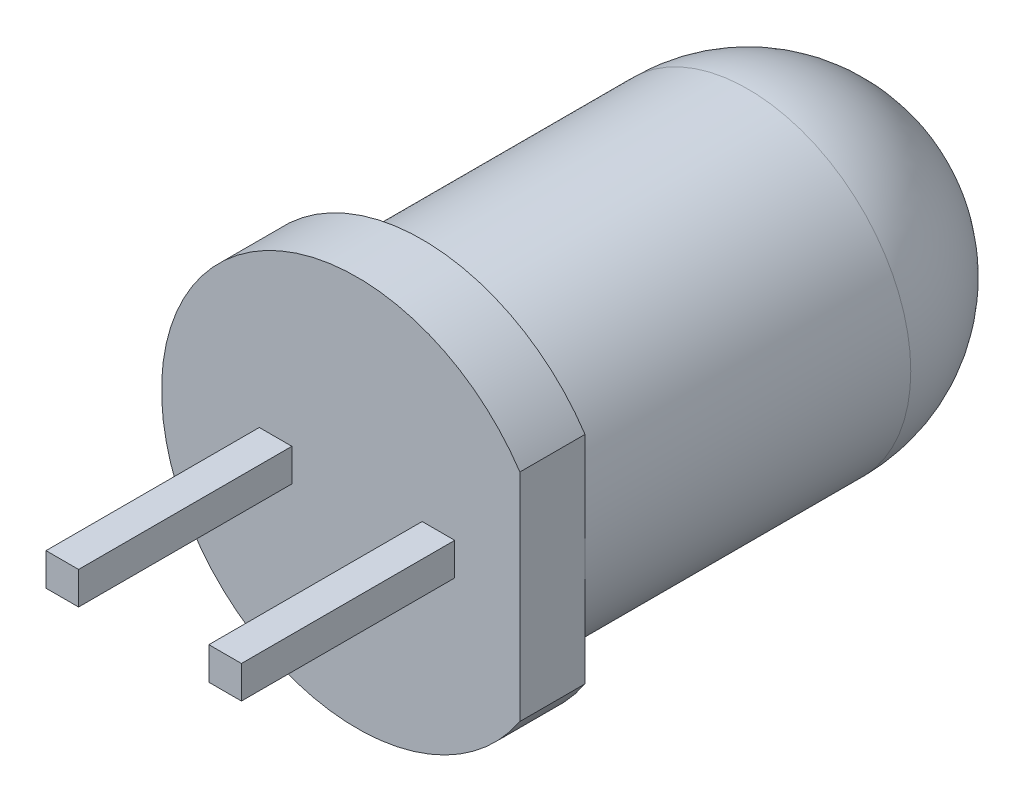
SolidWorks part; units mm, degrees
material "ABS"
ref_plane "Eest Vaade" through (0, 0, 0) normal (0, 0, 1) x (1, 0, 0)
ref_plane "Pealt Vaade" through (0, 0, 0) normal (0, 1, 0) x (1, 0, 0)
ref_plane "Külg Vaade" through (0, 0, 0) normal (1, 0, 0) x (0, 0, -1)
sketch "Sketch1" plane through (0, 0, 0) normal (0, 1, 0) x (1, 0, 0)
  line L0 (0, 8.0224) -> (0, -7.5746) construction
  line L1 (0, 4.7716) -> (0, -3.3955) construction
  line L2 (2.5, 4.7716) -> (2.5, -3.3955)
  line L3 (-2.5, 4.7716) -> (-2.5, -3.3955)
  line L5 (3, -1.2284) -> (-3, -1.2284)
  line L6 (3, -1.2284) -> (3, -0.2284)
  line L7 (3, -0.2284) -> (-3, -0.2284)
  line L8 (-3, -1.2284) -> (-3, -0.2284)
  line L9 (3, -1.2284) -> (-3, -0.2284) construction
  line L10 (3, -0.2284) -> (-3, -1.2284) construction
  arc A0 (2.5, 4.7716) -> (-2.5, 4.7716) centre (0, 4.7716) ccw
  arc A1 (-2.5, -3.3955) -> (2.5, -3.3955) centre (0, -3.3955) ccw
  point P5 (0, 0.688)
  point P10 (0, -0.7284)
  dimension "D1" = 5
  dimension "D2" = 1
  dimension "D3" = 6
  dimension "D4" = 8.5
sketch "Sketch2" plane through (0, 0, 0) normal (0, 1, 0) x (1, 0, 0)
  line L0 (0, 8.0224) -> (0, -7.5746) construction
  line L1 (-1.5, -0.2284) -> (-1, -0.2284)
  line L2 (-1.5, -0.2284) -> (-1.5, -29.2284)
  line L3 (-1.5, -29.2284) -> (-1, -29.2284)
  line L4 (-1, -0.2284) -> (-1, -29.2284)
  line L5 (1, -0.2284) -> (1.5, -0.2284)
  line L6 (1, -0.2284) -> (1, -27.2284)
  line L7 (1, -27.2284) -> (1.5, -27.2284)
  line L8 (1.5, -0.2284) -> (1.5, -27.2284)
  line L9 (3, -1.2284) -> (-3, -1.2284) construction
  line L10 (3, -0.2284) -> (-3, -0.2284) construction
  dimension "D1" = 0.5
  dimension "D2" = 0.5
  dimension "D3" = 3
  dimension "D4" = 1.5
  dimension "D5" = 26
  dimension "D6" = 28
sketch "Sketch4" plane through (0, 0, 0) normal (0, 1, 0) x (1, 0, 0)
  line L0 (0, 8.0224) -> (0, -7.5746) construction
  line L1 (-2.5, 4.7716) -> (-2.5, -3.3955) construction
  line L2 (3, -1.2284) -> (-3, -1.2284) construction
  line L3 (-3, -1.2284) -> (-3, -0.2284) construction
  line L5 (-2.5, 4.7716) -> (-2.5, -0.2284)
  line L6 (0, -1.2284) -> (-3, -1.2284)
  line L7 (-3, -1.2284) -> (-3, -0.2284)
  line L8 (3, -0.2284) -> (-3, -0.2284) construction
  line L9 (-2.5, -0.2284) -> (-3, -0.2284)
  line L10 (0, 7.2716) -> (0, -1.2284)
  arc A0 (2.5, 4.7716) -> (-2.5, 4.7716) centre (0, 4.7716) ccw construction
  arc A1 (0, 7.2716) -> (-2.5, 4.7716) centre (0, 4.7716) ccw
revolve "Revolve1" add sketch "Sketch4" angle 360 about L0
sketch "Sketch5" plane through (0, 0, 0) normal (0, 1, 0) x (1, 0, 0)
  line L0 (-1.5, -0.2284) -> (-1.5, -29.2284) construction
  line L1 (-1, -0.2284) -> (-1, -29.2284) construction
  line L2 (3, -0.2284) -> (-3, -0.2284) construction
  line L3 (-1.5, -29.2284) -> (-1, -29.2284) construction
  line L4 (1, -27.2284) -> (1.5, -27.2284) construction
  line L5 (1, -0.2284) -> (1, -27.2284) construction
  line L6 (1.5, -0.2284) -> (1.5, -27.2284) construction
  line L7 (-1.5, -0.2284) -> (-1.5, -29.2284)
  line L8 (-1, -0.2284) -> (-1, -29.2284)
  line L9 (1.5, -0.2284) -> (1, -0.2284)
  line L10 (-1.5, -29.2284) -> (-1, -29.2284)
  line L11 (1, -27.2284) -> (1.5, -27.2284)
  line L12 (1, -0.2284) -> (1, -27.2284)
  line L13 (1.5, -0.2284) -> (1.5, -27.2284)
  line L14 (-1, -0.2284) -> (-1.5, -0.2284)
extrude "Boss-Extrude1" add sketch "Sketch5" along normal mid plane 0.5
sketch "Sketch6" plane through (0, 0, 0) normal (0, 1, 0) x (1, 0, 0)
  line L0 (2.5, -0.2284) -> (2.5, 4.7716) construction
  line L1 (5.5891, 5.0424) -> (2.5, 5.0424)
  line L2 (5.5891, 5.0424) -> (5.5891, -6.6476)
  line L3 (5.5891, -6.6476) -> (2.5, -6.6476)
  line L4 (2.5, 5.0424) -> (2.5, -6.6476)
extrude "Cut-Extrude1" cut sketch "Sketch6" against normal mid plane 5
sketch "Sketch7" plane through (0, 0, 0) normal (0, 1, 0) x (1, 0, 0)
  line L0 (-7.7486, -4.5023) -> (9.3694, -4.5023)
  line L5 (9.3694, -4.5023) -> (9.3694, -32.3759)
  line L6 (9.3694, -32.3759) -> (-7.7486, -32.3759)
  line L7 (-7.7486, -32.3759) -> (-7.7486, -4.5023)
extrude "Cut-Extrude2" cut sketch "Sketch7" against normal through all both and the other way through all
